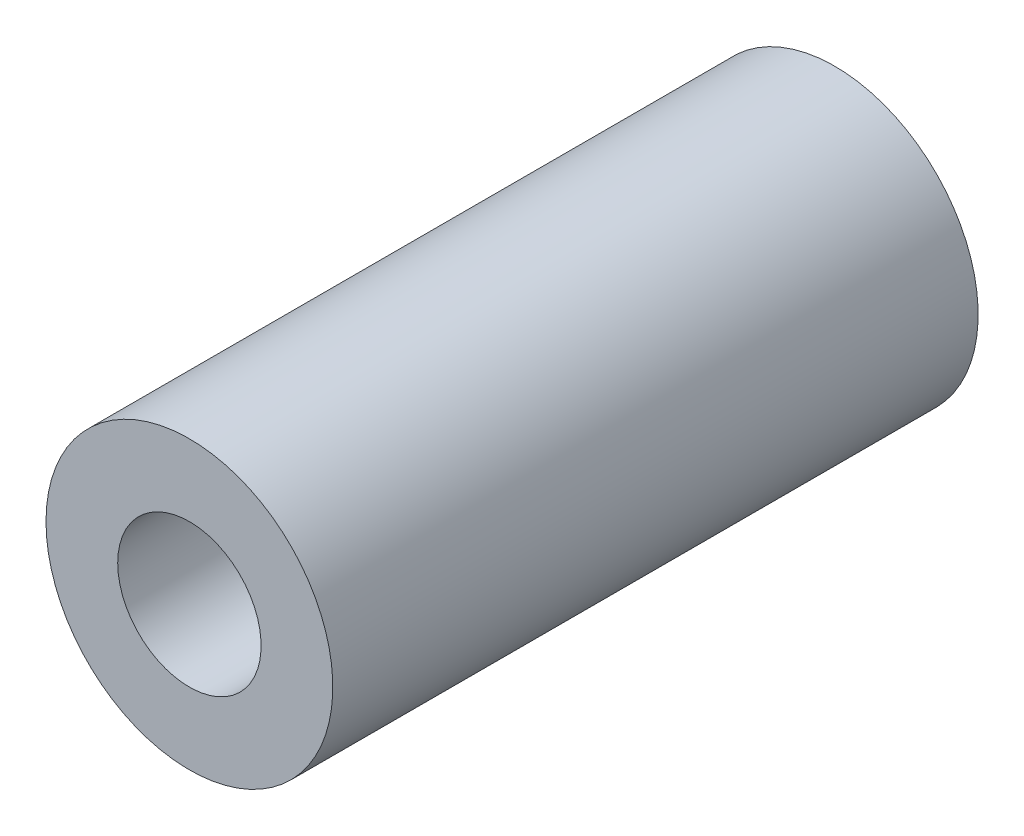
SolidWorks part; units mm, degrees
ref_plane "Plan de face" through (0, 0, 0) normal (0, 0, 1) x (1, 0, 0)
ref_plane "Plan de dessus" through (0, 0, 0) normal (0, 1, 0) x (1, 0, 0)
ref_plane "Plan de droite" through (0, 0, 0) normal (1, 0, 0) x (0, 0, -1)
sketch "Esquisse1" plane through (0, 0, 0) normal (0, 0, 1) x (1, 0, 0)
  circle A0 centre (0, 0) radius 10
  circle A1 centre (0, 0) radius 5
  dimension "D1" = 20
  dimension "D2" = 10
extrude "Boss.-Extru.1" add sketch "Esquisse1" along normal blind 45
